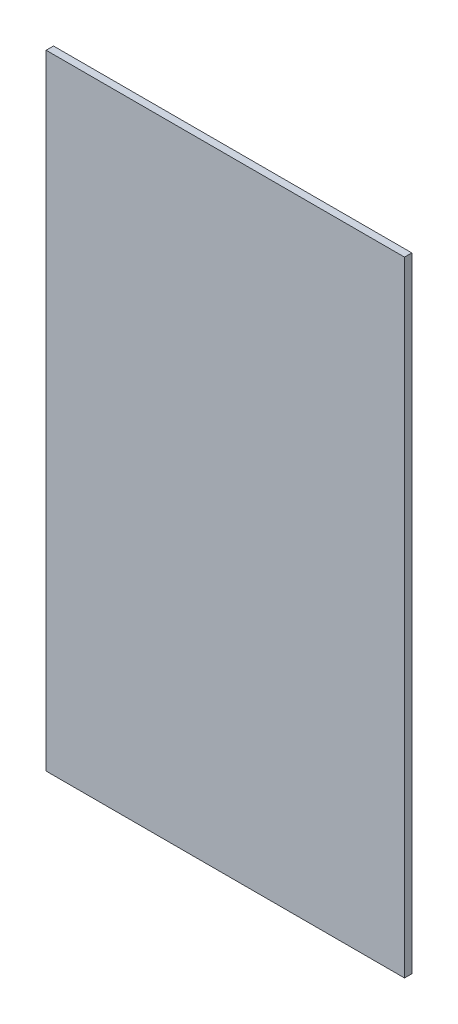
SolidWorks part; units mm, degrees
ref_plane "前视基准面" through (0, 0, 0) normal (0, 0, 1) x (1, 0, 0)
ref_plane "上视基准面" through (0, 0, 0) normal (0, 1, 0) x (1, 0, 0)
ref_plane "右视基准面" through (0, 0, 0) normal (1, 0, 0) x (0, 0, -1)
sketch "草图1" plane through (0, 0, 0) normal (0, 0, 1) x (1, 0, 0)
  line L1 (10, 0) -> (107.5745, 0)
  line L2 (10, 0) -> (10, 170)
  line L3 (10, 170) -> (107.5745, 170)
  line L4 (107.5745, 0) -> (107.5745, 170)
  line L5 (-192.1987, 170) -> (167.8013, 170) construction
extrude "凸台-拉伸1" add sketch "草图1" against normal blind 2
